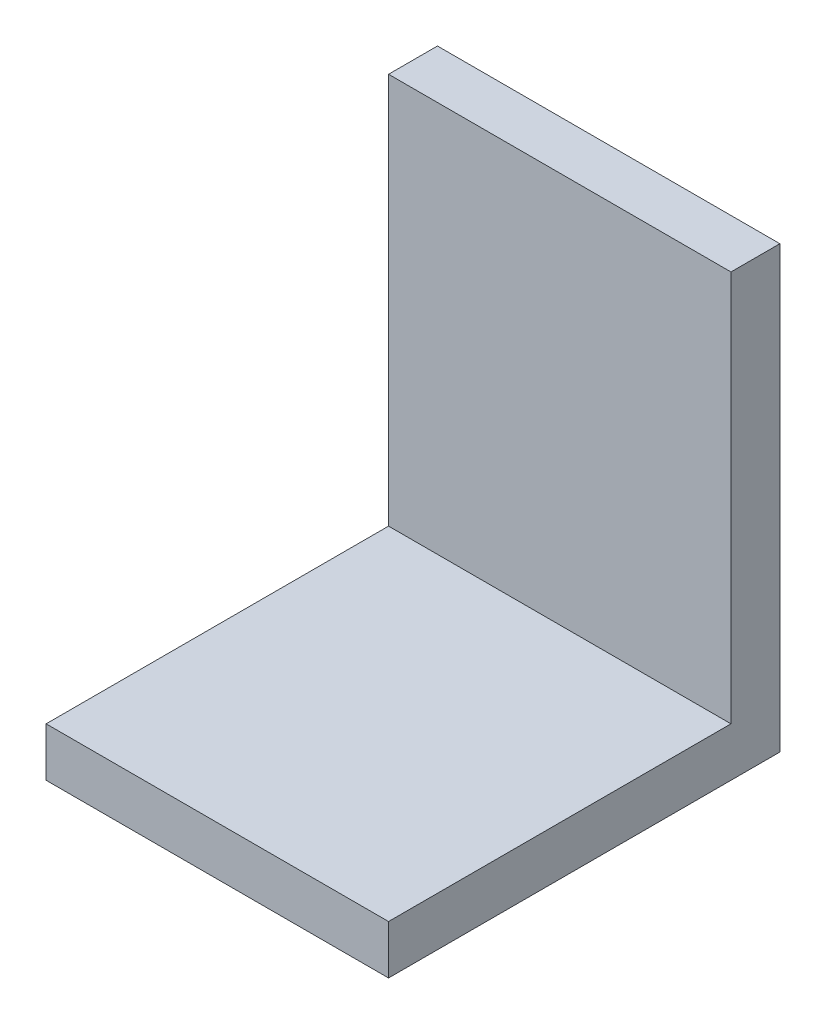
SolidWorks part; units mm, degrees
ref_plane "Front Plane" through (0, 0, 0) normal (0, 0, 1) x (1, 0, 0)
ref_plane "Top Plane" through (0, 0, 0) normal (0, 1, 0) x (1, 0, 0)
ref_plane "Right Plane" through (0, 0, 0) normal (1, 0, 0) x (0, 0, -1)
sketch "Sketch1" plane through (0, 0, 0) normal (0, 1, 0) x (1, 0, 0)
  line L0 (-55, 0) -> (55, 0) construction
  line L1 (12.2633, 0) -> (47.2633, 0)
  line L2 (12.2633, 0) -> (12.2633, 40)
  line L3 (12.2633, 40) -> (47.2633, 40)
  line L4 (47.2633, 0) -> (47.2633, 40)
  dimension "D1" = 40
  dimension "D2" = 35
extrude "Boss-Extrude1" add sketch "Sketch1" along normal blind 5
sketch "Sketch2" plane through (0, 5, 0) normal (0, 1, 0) x (1, 0, 0)
  line L0 (47.2633, 0) -> (47.2633, 40) construction
  line L1 (12.2633, 40) -> (47.2633, 40)
  line L2 (12.2633, 40) -> (12.2633, 35)
  line L3 (12.2633, 35) -> (47.2633, 35)
  line L4 (47.2633, 40) -> (47.2633, 35)
  dimension "D1" = 5
extrude "Boss-Extrude2" add sketch "Sketch2" along normal blind 40
